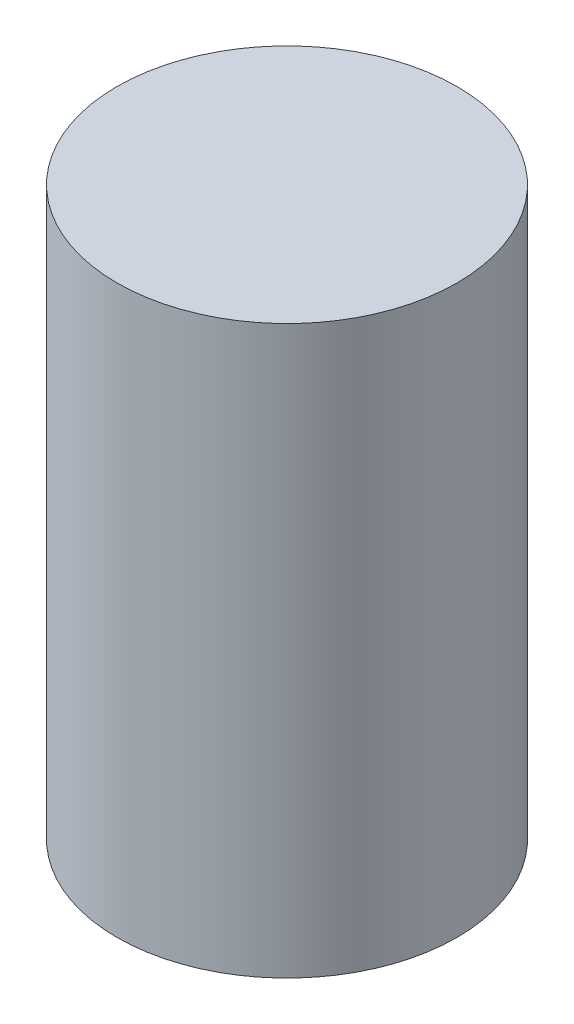
SolidWorks part; units mm, degrees
ref_plane "Front Plane" through (0, 0, 0) normal (0, 0, 1) x (1, 0, 0)
ref_plane "Top Plane" through (0, 0, 0) normal (0, 1, 0) x (1, 0, 0)
ref_plane "Right Plane" through (0, 0, 0) normal (1, 0, 0) x (0, 0, -1)
sketch "Sketch1" plane through (0, 0, 0) normal (0, 1, 0) x (1, 0, 0)
  circle A0 centre (0, 0) radius 0.9
  dimension "D1" = 1.8
extrude "Boss-Extrude1" add sketch "Sketch1" along normal blind 3
